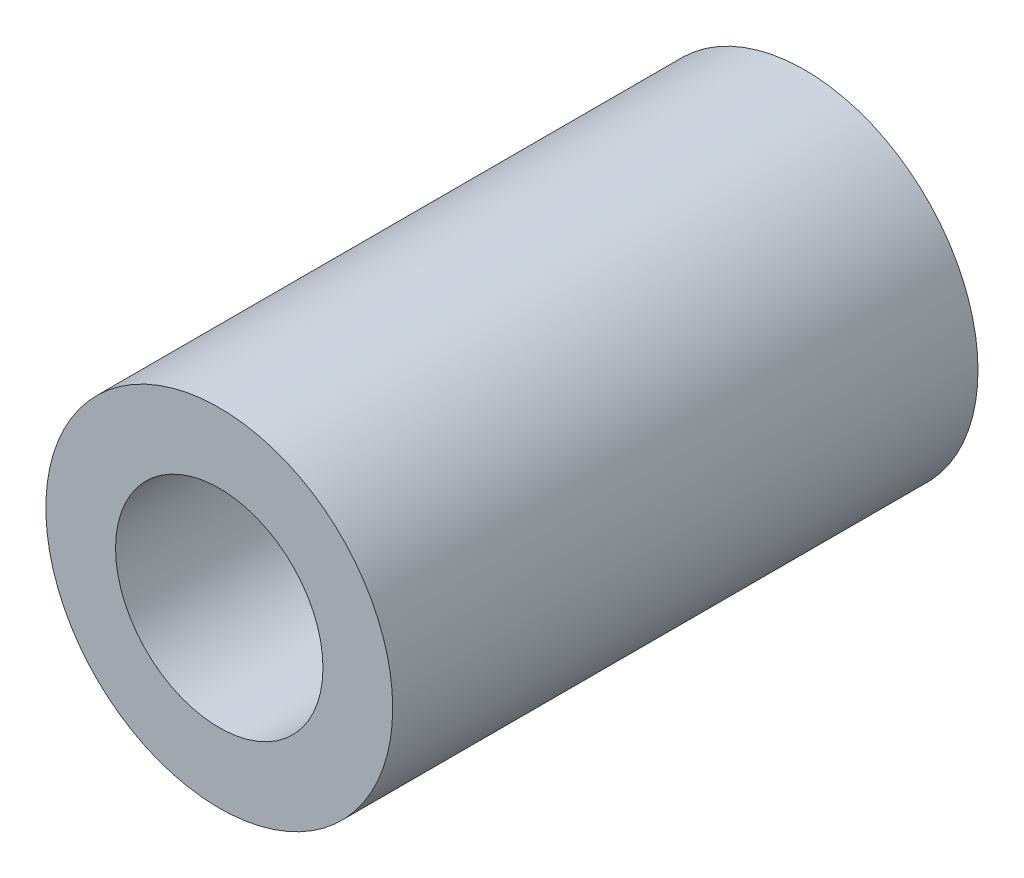
SolidWorks part; units mm, degrees
ref_plane "Front Plane" through (0, 0, 0) normal (0, 0, 1) x (1, 0, 0)
ref_plane "Top Plane" through (0, 0, 0) normal (0, 1, 0) x (1, 0, 0)
ref_plane "Right Plane" through (0, 0, 0) normal (1, 0, 0) x (0, 0, -1)
sketch "Sketch1" plane through (0, 0, 0) normal (0, 0, 1) x (1, 0, 0)
  circle A0 centre (0, 0) radius 3.175
  circle A1 centre (0, 0) radius 1.8986
  dimension "D1" = 6.35
  dimension "D2" = 3.7973
extrude "Boss-Extrude1" add sketch "Sketch1" along normal blind 10.7156
